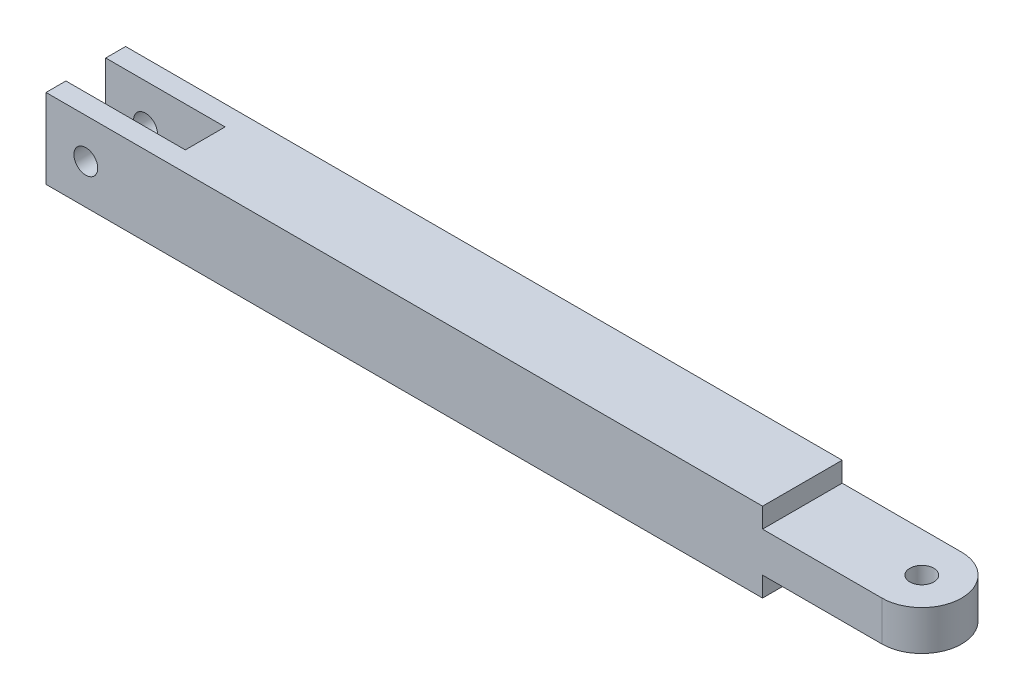
SolidWorks part; units mm, degrees
ref_plane "Alzado" through (0, 0, 0) normal (0, 0, 1) x (1, 0, 0)
ref_plane "Planta" through (0, 0, 0) normal (0, 1, 0) x (1, 0, 0)
ref_plane "Vista lateral" through (0, 0, 0) normal (1, 0, 0) x (0, 0, -1)
sketch "Croquis1" plane through (0, 0, 0) normal (0, 1, 0) x (1, 0, 0)
  line L0 (-50, 2.5) -> (-50, 5)
  line L1 (-50, -5) -> (50, -5)
  line L2 (-50, -5) -> (-50, -2.5)
  line L3 (-50, 5) -> (50, 5)
  line L4 (50, -5) -> (50, 5)
  line L5 (-50, -5) -> (50, 5) construction
  line L6 (-50, 5) -> (50, -5) construction
  line L7 (-50, 2.5) -> (-35, 2.5)
  line L9 (-50, -2.5) -> (-35, -2.5)
  line L10 (-35, 2.5) -> (-35, -2.5)
  point P0 (0, 0)
  dimension "D1" = 100
  dimension "D2" = 10
  dimension "D3" = 15
  dimension "D4" = 5
  dimension "D5" = 2.5
extrude "Saliente-Extruir1" add sketch "Croquis1" along normal blind 10
sketch "Croquis2" plane through (50, 0, 0) normal (1, 0, 0) x (0, 0, -1)
  line L0 (-5, 10) -> (-5, 0) construction
  line L1 (-5, 2.5) -> (5, 2.5)
  line L2 (-5, 2.5) -> (-5, 7.5)
  line L3 (-5, 7.5) -> (5, 7.5)
  line L4 (5, 2.5) -> (5, 7.5)
  line L5 (5, 10) -> (5, 0) construction
  line L6 (-5, 10) -> (5, 10) construction
  dimension "D1" = 5
  dimension "D2" = 2.5
extrude "Saliente-Extruir2" add sketch "Croquis2" along normal blind 10
sketch "Croquis4" plane through (0, 7.5, 0) normal (0, 1, 0) x (1, 0, 0)
  line L0 (50, 0) -> (60, 0) construction
  line L3 (50, 5) -> (50, -5) construction
  line L4 (60, 5) -> (60, -5) construction
  line L5 (55, 5) -> (55, 11.0292)
  line L6 (55, 11.0292) -> (66.1427, 11.0292)
  line L7 (66.1427, 11.0292) -> (66.1427, -12.9017)
  line L8 (66.1427, -12.9017) -> (58.7574, -12.9017)
  line L9 (58.7574, -12.9017) -> (55, -5)
  arc A0 (55, -5) -> (55, 5) centre (55, 0) ccw
  circle A1 centre (55, 0) radius 1.5
  dimension "D1" = 3
extrude "Cortar-Extruir1" cut sketch "Croquis4" against normal blind 10
sketch "Croquis5" plane through (0, 0, 2.5) normal (0, 0, -1) x (-1, 0, 0)
  line L0 (50, 5) -> (40, 5) construction
  line L1 (50, 10) -> (50, 0) construction
  circle A0 centre (45, 5) radius 1.5
  dimension "D2" = 3
  dimension "D1" = 10
extrude "Cortar-Extruir2" cut sketch "Croquis5" against normal mid plane 19
sketch "Sketch1" plane through (50, 0, 0) normal (1, 0, 0) x (0, 0, -1)
  line L4 (-5, 7.5) -> (5, 7.5)
  line L5 (5, 7.5) -> (5, 10)
  line L6 (5, 10) -> (-5, 10)
  line L7 (-5, 10) -> (-5, 7.5)
  line L8 (-5, 7.5) -> (5, 7.5)
  line L9 (5, 7.5) -> (5, 10)
  line L10 (5, 10) -> (-5, 10)
  line L11 (-5, 10) -> (-5, 7.5)
  line L12 (5, 2.5) -> (-5, 2.5)
  line L13 (-5, 2.5) -> (-5, 0)
  line L14 (-5, 0) -> (5, 0)
  line L15 (5, 0) -> (5, 2.5)
  line L16 (5, 2.5) -> (-5, 2.5)
  line L17 (-5, 2.5) -> (-5, 0)
  line L18 (-5, 0) -> (5, 0)
  line L19 (5, 0) -> (5, 2.5)
  dimension "D1" = 0
  dimension "D2" = 0
extrude "Cut-Extrude1" cut sketch "Sketch1" against normal blind 10
